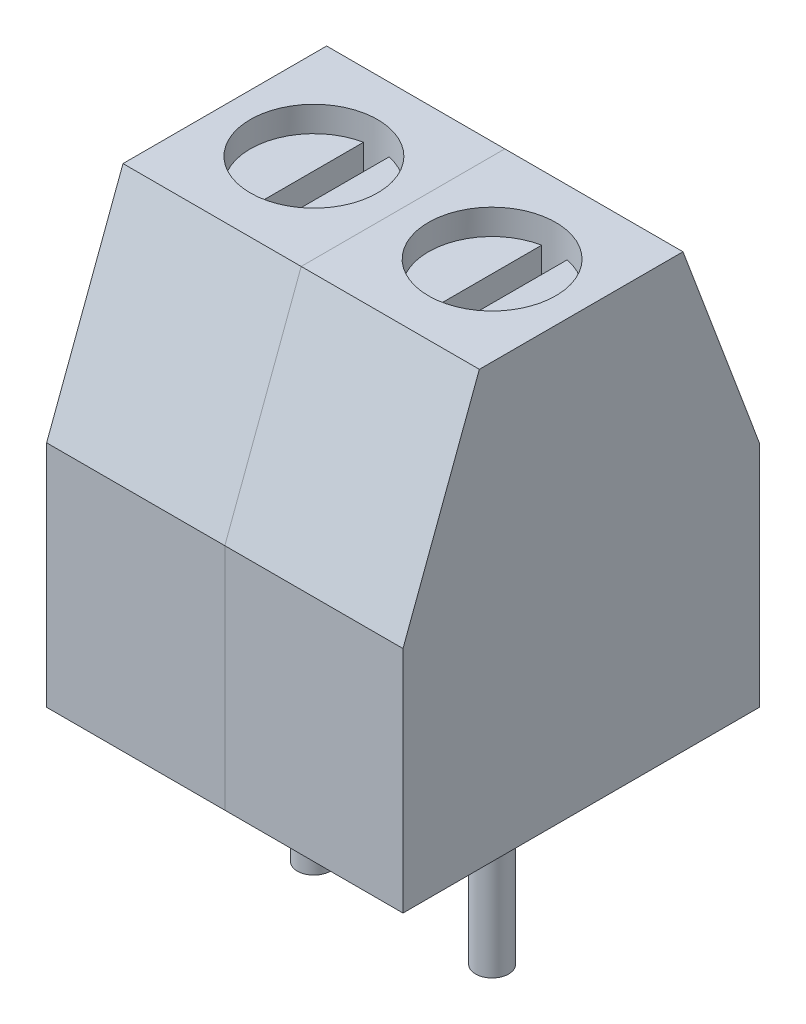
SolidWorks part; units mm, degrees
ref_plane "정면" through (0, 0, 0) normal (0, 0, 1) x (1, 0, 0)
ref_plane "윗면" through (0, 0, 0) normal (0, 1, 0) x (1, 0, 0)
ref_plane "우측면" through (0, 0, 0) normal (1, 0, 0) x (0, 0, -1)
sketch "스케치1" plane through (0, 0, 0) normal (1, 0, 0) x (0, 0, -1)
  line L0 (0, 4.5) -> (0, 8.5) construction
  line L1 (0, 0) -> (7, 0)
  line L2 (0, 0) -> (0, 4.5)
  line L3 (0, 8.5) -> (7, 8.5) construction
  line L4 (7, 0) -> (7, 4.5)
  line L5 (1.5, 8.5) -> (5.5, 8.5)
  line L6 (1.5, 8.5) -> (0, 4.5)
  line L7 (5.5, 8.5) -> (7, 4.5)
  line L8 (7, 4.5) -> (7, 8.5) construction
  line L9 (0, 4.5) -> (7, 4.5) construction
  point P10 (3.5, 8.5)
  dimension "D1" = 4
  dimension "D2" = 7
  dimension "D3" = 8.5
  dimension "D4" = 4.5
extrude "보스-돌출1" add sketch "스케치1" along normal blind 3.5
sketch "스케치3" plane through (0, 0, -7) normal (0, 0, -1) x (-1, 0, 0)
  line L0 (-3.5, 4.5) -> (0, 4.5) construction
  line L1 (-3.25, 0.5) -> (-0.25, 0.5)
  line L2 (-3.25, 0.5) -> (-3.25, 4.5)
  line L3 (-3.25, 4.5) -> (-0.25, 4.5)
  line L4 (-0.25, 0.5) -> (-0.25, 4.5)
  line L5 (-3.5, 0) -> (-3.5, 4.5) construction
  line L6 (0, 0) -> (0, 4.5) construction
  line L7 (-3.5, 0) -> (0, 0) construction
  dimension "D1" = 0.25
  dimension "D2" = 0.25
  dimension "D3" = 0.5
extrude "컷-돌출1" cut sketch "스케치3" against normal blind 1.5
sketch "스케치4" plane through (0, 8.5, 0) normal (0, 1, 0) x (1, 0, 0)
  circle A0 centre (1.75, 3.5) radius 1.25
extrude "컷-돌출2" cut sketch "스케치4" against normal blind 0.5
sketch "스케치5" plane through (0, 8, 0) normal (0, 1, 0) x (1, 0, 0)
  line L2 (1.5001, 4.7248) -> (1.5001, 2.2752)
  line L4 (1.9999, 4.7248) -> (1.9999, 2.2752)
  line L5 (1.5001, 4.7248) -> (1.9999, 2.2752) construction
  line L6 (1.5001, 2.2752) -> (1.9999, 4.7248) construction
  arc A0 (1.5001, 2.2752) -> (1.9999, 2.2752) centre (1.75, 3.5) ccw
  circle A1 centre (1.75, 3.5) radius 1.25
  arc A2 (1.9999, 4.7248) -> (1.5001, 4.7248) centre (1.75, 3.5) ccw
  dimension "D1" = 0
extrude "컷-돌출3" cut sketch "스케치5" against normal blind 0.5
sketch "스케치7" plane through (0, 0, -5.5) normal (0, 0, -1) x (-1, 0, 0)
  line L0 (-3.25, 4.5) -> (-3.25, 0.5) construction
  line L1 (-3.25, 0.5) -> (-0.25, 0.5) construction
  circle A0 centre (-1.75, 2) radius 1
  dimension "D1" = 1.5
  dimension "D2" = 2
  dimension "D3" = 1.5
extrude "컷-돌출4" cut sketch "스케치7" against normal blind 3
pattern_linear "선형 패턴1" [suppressed] count 3 spacing 3.5
sketch "Sketch1" plane through (0, 0, 0) normal (0, -1, 0) x (1, 0, 0)
  line L4 (0, 0) -> (0, -7)
  line L5 (0, -7) -> (3.5, -7)
  line L6 (3.5, -7) -> (3.5, 0)
  line L7 (3.5, 0) -> (0, 0)
  line L8 (0, 0) -> (0, -7)
  line L9 (0, -7) -> (3.5, -7)
  line L10 (3.5, -7) -> (3.5, 0)
  line L11 (3.5, 0) -> (0, 0)
  circle A0 centre (1.75, -3.5) radius 0.325
  point P6 (0, 0)
  point P7 (0, 0)
  dimension "D2" = 1.75
  dimension "D3" = 3.5
  dimension "D4" = 7
  dimension "D5" = 3.5
  dimension "D1" = 0
extrude "Boss-Extrude1" add sketch "Sketch1" along normal blind 3.5 contours A0
pattern_linear "LPattern1" count 2 spacing 3.5 along (1, 0, 0) of bodies 108
